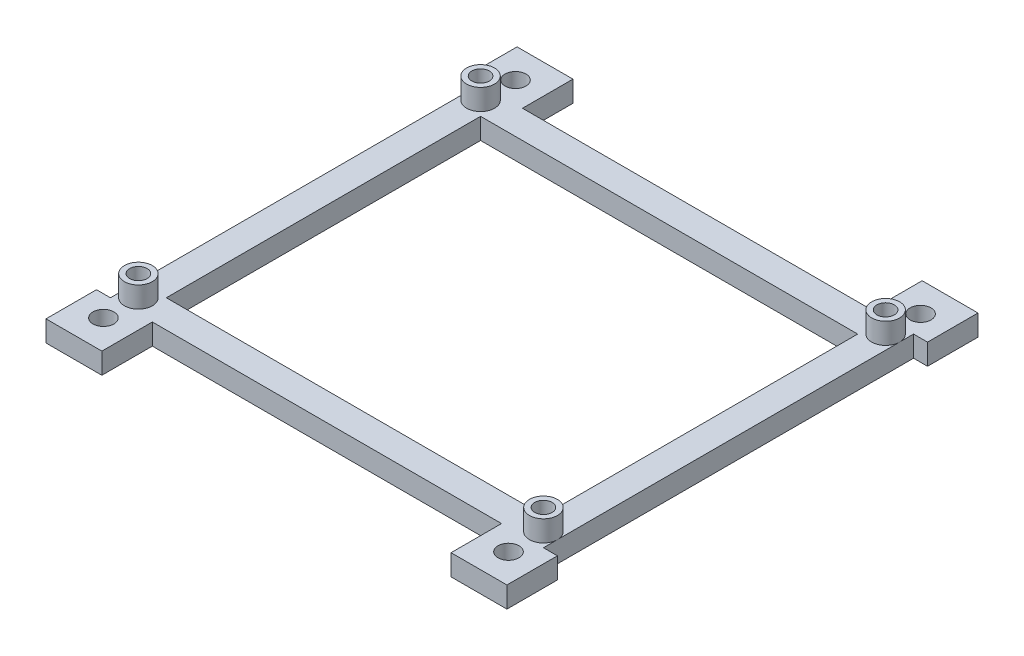
SolidWorks part; units mm, degrees
ref_plane "前视基准面" through (0, 0, 0) normal (0, 0, 1) x (1, 0, 0)
ref_plane "上视基准面" through (0, 0, 0) normal (0, 1, 0) x (1, 0, 0)
ref_plane "右视基准面" through (0, 0, 0) normal (1, 0, 0) x (0, 0, -1)
other "Configuration Table"
sketch "草图1" plane through (0, 0, 0) normal (0, 1, 0) x (1, 0, 0)
  line L0 (-31, 24.5) -> (-31, -24.5)
  line L1 (-29, 24.5) -> (29, 24.5) construction
  line L2 (-29, 24.5) -> (-29, -24.5) construction
  line L3 (-29, -24.5) -> (29, -24.5) construction
  line L4 (29, 24.5) -> (29, -24.5) construction
  line L5 (-29, 24.5) -> (29, -24.5) construction
  line L6 (-29, -24.5) -> (29, 24.5) construction
  line L7 (-29, 26.5) -> (29, 26.5)
  line L8 (31, 24.5) -> (31, -24.5)
  line L9 (-29, -26.5) -> (29, -26.5)
  line L10 (-27, 24.5) -> (-27, -24.5)
  line L11 (-29, 22.5) -> (29, 22.5)
  line L12 (27, 24.5) -> (27, -24.5)
  line L13 (-29, -22.5) -> (29, -22.5)
  circle A0 centre (-29, 24.5) radius 1.25
  circle A1 centre (29, 24.5) radius 1.25
  circle A2 centre (-29, -24.5) radius 1.25
  circle A3 centre (29, -24.5) radius 1.25
  circle A4 centre (-29, 24.5) radius 2
  circle A5 centre (-29, -24.5) radius 2
  circle A6 centre (29, 24.5) radius 2
  circle A7 centre (29, -24.5) radius 2
  point P0 (0, 0)
  dimension "D3" = 2.5
  dimension "D4" = 2.5
  dimension "D5" = 2.5
  dimension "D6" = 2.5
  dimension "D7" = 4
  dimension "D8" = 4
  dimension "D9" = 4
  dimension "D10" = 4
  dimension "D1" = 49
  dimension "D2" = 58
extrude "凸台-拉伸1" add sketch "草图1" along normal blind 3 contours A7 L12 L13 L10 A5 L9 | A7 L13 L12 | A7 A3 | A7 L8 A6 L11 L12 L13 | A5 L13 L10 L11 A4 L0 | A5 A2 | A5 L10 L13 | A6 L12 L11 | A6 A1 | A6 L7 A4 L10 L11 L12 | A4 L11 L10 | A4 A0
sketch "草图2" plane through (0, 3, 0) normal (0, 1, 0) x (1, 0, 0)
  circle A0 centre (-29, 24.5) radius 1.25
  circle A1 centre (-29, 24.5) radius 2
  circle A2 centre (29, 24.5) radius 1.25
  circle A3 centre (29, 24.5) radius 2
  circle A4 centre (-29, -24.5) radius 1.25
  circle A5 centre (-29, -24.5) radius 2
  circle A6 centre (29, -24.5) radius 1.25
  circle A7 centre (29, -24.5) radius 2
extrude "凸台-拉伸2" add sketch "草图2" along normal blind 3
sketch "草图3" plane through (0, 0, 0) normal (0, -1, 0) x (1, 0, 0)
  line L0 (-29, 26.5) -> (-29, 29.5) construction
  line L1 (-31, 24.5) -> (-31, 31.7272)
  line L2 (-31, 31.7272) -> (-27, 31.7272)
  line L3 (-27, 31.7272) -> (-27, 26.5)
  line L4 (-29, 26.5) -> (29, 26.5) construction
  line L5 (-29, 26.5) -> (-27, 26.5)
  line L6 (0, 26.5) -> (0, -26.5) construction
  line L7 (-29, -26.5) -> (29, -26.5) construction
  line L8 (-31, 0) -> (31, 0) construction
  line L9 (-31, -24.5) -> (-31, 24.5) construction
  line L10 (31, -24.5) -> (31, 24.5) construction
  line L11 (29, 26.5) -> (27, 26.5)
  line L12 (27, 31.7272) -> (27, 26.5)
  line L13 (31, 31.7272) -> (27, 31.7272)
  line L14 (31, 24.5) -> (31, 31.7272)
  line L15 (31, -24.5) -> (31, -31.7272)
  line L16 (31, -31.7272) -> (27, -31.7272)
  line L17 (27, -31.7272) -> (27, -26.5)
  line L18 (29, -26.5) -> (27, -26.5)
  line L19 (-29, -26.5) -> (-29, -29.5) construction
  line L20 (-29, -26.5) -> (-27, -26.5)
  line L21 (-27, -31.7272) -> (-27, -26.5)
  line L22 (-31, -31.7272) -> (-27, -31.7272)
  line L23 (-31, -24.5) -> (-31, -31.7272)
  circle A0 centre (-29, 29.5) radius 1.5
  arc A1 (-29, 26.5) -> (-31, 24.5) centre (-29, 24.5) ccw construction
  arc A2 (-29, 26.5) -> (-31, 24.5) centre (-29, 24.5) ccw
  arc A3 (29, 26.5) -> (31, 24.5) centre (29, 24.5) cw
  circle A4 centre (29, 29.5) radius 1.5
  circle A5 centre (29, -29.5) radius 1.5
  arc A6 (29, -26.5) -> (31, -24.5) centre (29, -24.5) ccw
  arc A7 (-29, -26.5) -> (-31, -24.5) centre (-29, -24.5) cw
  circle A8 centre (-29, -29.5) radius 1.5
  dimension "D2" = 3
  dimension "D1" = 3
extrude "凸台-拉伸3" add sketch "草图3" against normal blind 3
sketch "草图4" plane through (0, 0, 0) normal (0, -1, 0) x (1, 0, 0)
  line L0 (-31, 26.5) -> (-33, 26.5)
  line L1 (-31, -31.7272) -> (-31, 31.7272) construction
  line L2 (-33, 26.5) -> (-33, 31.7272)
  line L3 (-27, 26.5) -> (-25, 26.5)
  line L4 (-27, 26.5) -> (27, 26.5) construction
  line L5 (-33, 31.7272) -> (-33, 33.7272)
  line L6 (-33, 33.7272) -> (-25, 33.7272)
  line L7 (-25, 33.7272) -> (-25, 26.5)
  line L8 (-31, 26.5) -> (-31, 31.7272)
  line L9 (-31, 31.7272) -> (-27, 31.7272)
  line L10 (-27, 31.7272) -> (-27, 26.5)
  line L11 (0, 26.5) -> (0, -26.5) construction
  line L12 (-27, -26.5) -> (27, -26.5) construction
  line L13 (-31, 0) -> (31, 0) construction
  line L14 (31, -31.7272) -> (31, 31.7272) construction
  line L15 (27, 31.7272) -> (27, 26.5)
  line L16 (31, 31.7272) -> (27, 31.7272)
  line L17 (31, 26.5) -> (31, 31.7272)
  line L18 (25, 33.7272) -> (25, 26.5)
  line L19 (33, 33.7272) -> (25, 33.7272)
  line L20 (33, 31.7272) -> (33, 33.7272)
  line L21 (27, 26.5) -> (25, 26.5)
  line L22 (33, 26.5) -> (33, 31.7272)
  line L23 (31, 26.5) -> (33, 26.5)
  line L24 (31, -26.5) -> (33, -26.5)
  line L25 (33, -26.5) -> (33, -31.7272)
  line L26 (27, -26.5) -> (25, -26.5)
  line L27 (33, -31.7272) -> (33, -33.7272)
  line L28 (33, -33.7272) -> (25, -33.7272)
  line L29 (25, -33.7272) -> (25, -26.5)
  line L30 (31, -26.5) -> (31, -31.7272)
  line L31 (31, -31.7272) -> (27, -31.7272)
  line L32 (27, -31.7272) -> (27, -26.5)
  line L33 (-27, -31.7272) -> (-27, -26.5)
  line L34 (-31, -31.7272) -> (-27, -31.7272)
  line L35 (-31, -26.5) -> (-31, -31.7272)
  line L36 (-25, -33.7272) -> (-25, -26.5)
  line L37 (-33, -33.7272) -> (-25, -33.7272)
  line L38 (-33, -31.7272) -> (-33, -33.7272)
  line L39 (-27, -26.5) -> (-25, -26.5)
  line L40 (-33, -26.5) -> (-33, -31.7272)
  line L41 (-31, -26.5) -> (-33, -26.5)
  dimension "D1" = 2
  dimension "D2" = 2
  dimension "D3" = 2
extrude "凸台-拉伸4" add sketch "草图4" against normal blind 3
